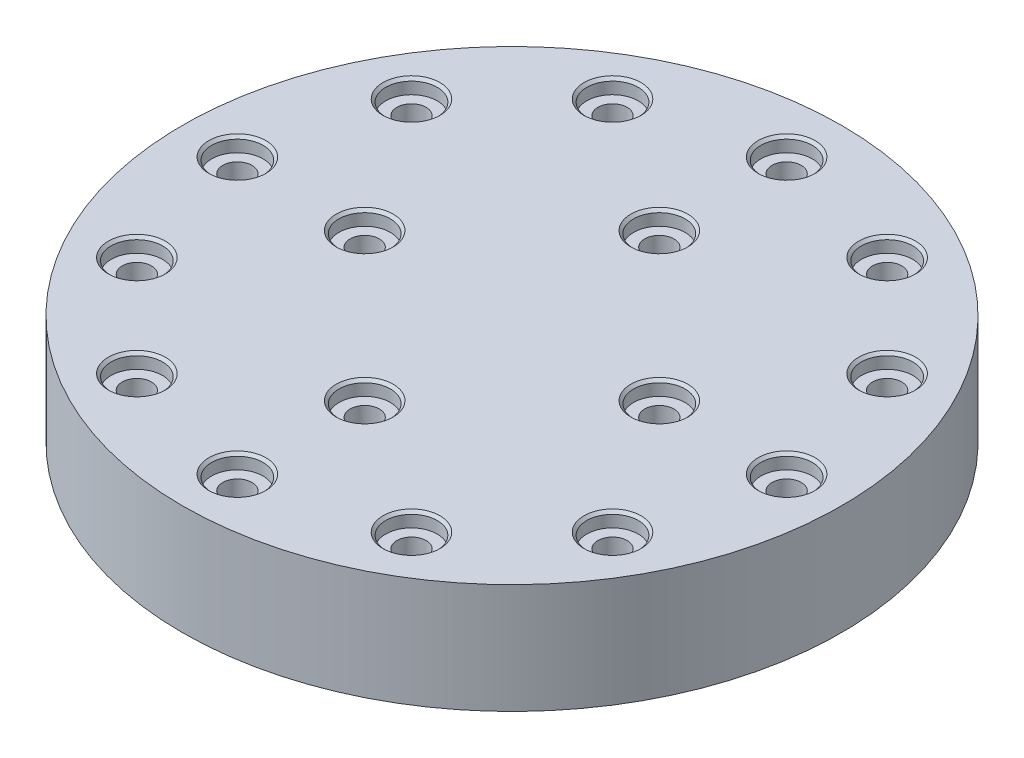
SolidWorks part; units mm, degrees
ref_plane "Front Plane" through (0, 0, 0) normal (0, 0, 1) x (1, 0, 0)
ref_plane "Top Plane" through (0, 0, 0) normal (0, 1, 0) x (1, 0, 0)
ref_plane "Right Plane" through (0, 0, 0) normal (1, 0, 0) x (0, 0, -1)
sketch "Sketch1" plane through (0, 0, 0) normal (0, 1, 0) x (1, 0, 0)
  circle A0 centre (0, 0) radius 76.2
  dimension "D1" = 152.4
extrude "Boss-Extrude1" add sketch "Sketch1" against normal blind 25.4
sketch "Sketch2" plane through (0, 0, 0) normal (0, 1, 0) x (1, 0, 0)
  line L1 (-50.8, -38.1) -> (50.8, -38.1)
  line L2 (-50.8, -38.1) -> (-50.8, 38.1)
  line L3 (-50.8, 38.1) -> (50.8, 38.1)
  line L4 (50.8, -38.1) -> (50.8, 38.1)
  line L5 (-50.8, -38.1) -> (50.8, 38.1) construction
  line L6 (-50.8, 38.1) -> (50.8, -38.1) construction
  point P0 (0, 0)
  dimension "D1" = 76.2
  dimension "D2" = 101.6
hole_wizard "CBORE for 3/8 Button Head Cap Screw1" positions "Sketch3" profile "Sketch4" counterbore size "3/8" standard "ANSI Inch"
sketch "Sketch3" plane through (0, 0, 0) normal (0, 1, 0) x (1, 0, 0)
  point P2 (60.5813, 11.5529)
  point P4 (16.1466, -48.9641)
  point P6 (8.0149, -18.8719)
  point P10 (-22.7229, 30.9885)
  point P16 (16.1466, 47.7341)
sketch "Sketch4" plane through (60.5813, 0, -11.5529) normal (1, 0, 0) x (0, 0, 1)
  line L0 (0, 0) -> (0, 25.4)
  line L1 (0, 25.4) -> (5.0419, 25.4)
  line L3 (5.0419, 25.4) -> (5.0419, 5.0546)
  line L4 (8.7312, 5.0546) -> (5.0419, 5.0546)
  line L5 (8.7312, 5.0546) -> (8.7312, 0.635)
  line L6 (8.7312, 0.635) -> (9.3662, 0)
  line L7 (9.3662, 0) -> (0, 0)
  line L8 (-8.7312, 0.635) -> (-9.3662, 0) construction
  line L11 (0, -6.35) -> (0, 107.95) construction
  dimension "Thru Hole Dia." = 10.0838
  dimension "Thru Hole Depth" = 25.4
  dimension "C'Bore Dia." = 17.4625
  dimension "C'Bore Depth" = 5.0546
  dimension "Near C'Sink Dia." = 18.7325
  dimension "Near C'Sink Angle" = 90
sketch "Sketch11" plane through (0, 0, 0) normal (0, 1, 0) x (1, 0, 0)
  line L0 (0, 0) -> (34.0615, 0) construction
  line L1 (0, 0) -> (0, -34.0615) construction
  line L2 (0, 0) -> (-34.0615, 0) construction
  line L3 (0, 0) -> (0, 34.0615) construction
  circle A0 centre (0, 0) radius 34.0615 construction
hole_wizard "CBORE for 1/4 Button Head Cap Screw2" positions "Sketch12" profile "Sketch13" counterbore size "1/4" standard "ANSI Inch" end condition up to next
sketch "Sketch12" plane through (0, 0, 0) normal (0, 1, 0) x (1, 0, 0)
  point P0 (-34.0615, 0)
  point P3 (0, 34.0615)
  point P6 (34.0615, 0)
  point P9 (0, -34.0615)
sketch "Sketch13" plane through (-34.0615, 0, 0) normal (1, 0, 0) x (0, 0, 1)
  line L0 (0, 0) -> (0, 25.4)
  line L1 (0, 25.4) -> (3.3782, 25.4)
  line L3 (3.3782, 25.4) -> (3.3782, 3.3528)
  line L4 (5.9538, 3.3528) -> (3.3782, 3.3528)
  line L5 (5.9538, 3.3528) -> (5.9538, 0.635)
  line L6 (5.9538, 0.635) -> (6.5888, 0)
  line L7 (6.5888, 0) -> (0, 0)
  line L8 (-5.9538, 0.635) -> (-6.5888, 0) construction
  line L11 (0, -6.35) -> (0, 107.95) construction
  dimension "Thru Hole Dia." = 6.7564
  dimension "Thru Hole Depth" = 25.4
  dimension "C'Bore Dia." = 11.9075
  dimension "C'Bore Depth" = 3.3528
  dimension "Near C'Sink Dia." = 13.1775
  dimension "Near C'Sink Angle" = 90
sketch "Sketch14" plane through (0, 0, 0) normal (0, 1, 0) x (1, 0, 0)
  line L0 (0, 0) -> (63.5, 0) construction
  circle A2 centre (0, 0) radius 76.2 construction
  dimension "D1" = 12.7
hole_wizard "CBORE for 1/4 Button Head Cap Screw3" positions "Sketch15" profile "Sketch16" counterbore size "1/4" standard "ANSI Inch" end condition up to next
sketch "Sketch15" plane through (0, 0, 0) normal (0, 1, 0) x (1, 0, 0)
  point P0 (63.5, 0)
sketch "Sketch16" plane through (63.5, 0, 0) normal (1, 0, 0) x (0, 0, 1)
  line L0 (0, 0) -> (0, 25.4)
  line L1 (0, 25.4) -> (3.3782, 25.4)
  line L3 (3.3782, 25.4) -> (3.3782, 3.3528)
  line L4 (5.9538, 3.3528) -> (3.3782, 3.3528)
  line L5 (5.9538, 3.3528) -> (5.9538, 0.635)
  line L6 (5.9538, 0.635) -> (6.5888, 0)
  line L7 (6.5888, 0) -> (0, 0)
  line L8 (-5.9538, 0.635) -> (-6.5888, 0) construction
  line L11 (0, -6.35) -> (0, 107.95) construction
  dimension "Thru Hole Dia." = 6.7564
  dimension "Thru Hole Depth" = 25.4
  dimension "C'Bore Dia." = 11.9075
  dimension "C'Bore Depth" = 3.3528
  dimension "Near C'Sink Dia." = 13.1775
  dimension "Near C'Sink Angle" = 90
pattern_circular "CirPattern1" count 12 over 360 about axis through (0, 0, 0) along (0, 1, 0) of "CBORE for 1/4 Button Head Cap Screw3"
